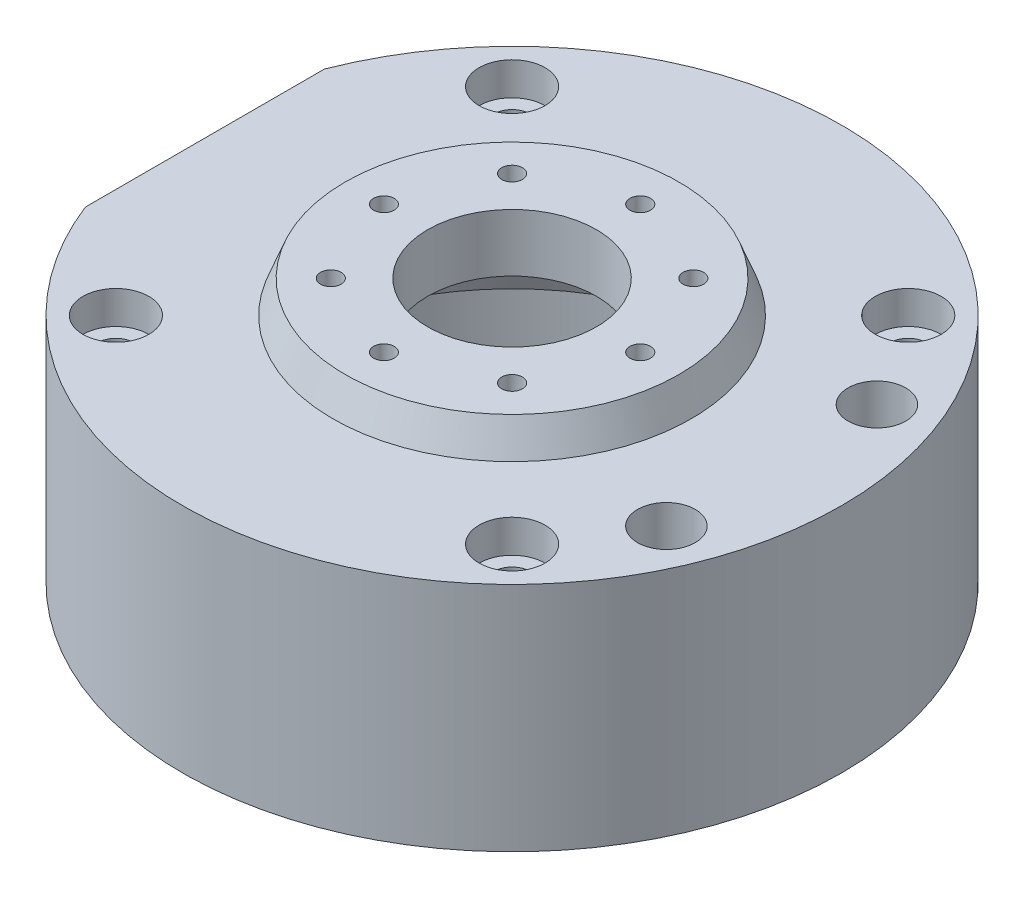
SolidWorks part; units mm, degrees
ref_plane "Front Plane" through (0, 0, 0) normal (0, 0, 1) x (1, 0, 0)
ref_plane "Top Plane" through (0, 0, 0) normal (0, 1, 0) x (1, 0, 0)
ref_plane "Right Plane" through (0, 0, 0) normal (1, 0, 0) x (0, 0, -1)
sketch "Sketch1" plane through (0, 0, 0) normal (0, 0, 1) x (1, 0, 0)
  line L0 (0, 10.5736) -> (0, -6.4838) construction
  line L1 (10.235, 32) -> (10.235, 25)
  line L2 (10.235, 25) -> (25, 25)
  line L3 (25, 25) -> (29.55, 10)
  line L4 (29.55, 10) -> (29.55, 0)
  line L5 (29.55, 0) -> (40, 0)
  line L6 (40, 0) -> (40, 28.1)
  line L7 (40, 28.1) -> (21.75, 28.1)
  line L8 (21.75, 28.1) -> (20.25, 32)
  line L9 (20.25, 32) -> (10.235, 32)
  dimension "D1" = 80
  dimension "D2" = 59.1
  dimension "D3" = 10
  dimension "D4" = 50
  dimension "D5" = 25
  dimension "D6" = 28.1
  dimension "D7" = 32
  dimension "D8" = 20.47
  dimension "D9" = 40.5
  dimension "D10" = 43.5
revolve "Revolve1" add sketch "Sketch1" angle 360 about L0
sketch "Sketch2" plane through (0, 28.1, 0) normal (0, 1, 0) x (1, 0, 0)
  line L1 (24.0416, -24.0416) -> (-24.0416, -24.0416) construction
  line L2 (24.0416, -24.0416) -> (24.0416, 24.0416) construction
  line L3 (24.0416, 24.0416) -> (-24.0416, 24.0416) construction
  line L4 (-24.0416, -24.0416) -> (-24.0416, 24.0416) construction
  line L5 (24.0416, -24.0416) -> (-24.0416, 24.0416) construction
  line L6 (24.0416, 24.0416) -> (-24.0416, -24.0416) construction
  point P0 (0, 0)
  dimension "D1" = 68
hole_wizard "CBORE for M4 SHCS1" positions "Sketch3" profile "Sketch4" counterbore size "M4" standard "ANSI Metric" end condition through all
sketch "Sketch3" plane through (0, 28.1, 0) normal (0, 1, 0) x (1, 0, 0)
  point P0 (-24.0416, 24.0416)
  point P3 (24.0416, 24.0416)
  point P6 (24.0416, -24.0416)
  point P9 (-24.0416, -24.0416)
sketch "Sketch4" plane through (-24.0416, 28.1, -24.0416) normal (1, 0, 0) x (0, 0, 1)
  line L0 (0, 0) -> (0, 28.1)
  line L1 (0, 28.1) -> (2.25, 28.1)
  line L3 (2.25, 28.1) -> (2.25, 4)
  line L4 (2.25, 4) -> (4, 4)
  line L5 (4, 4) -> (4, 0)
  line L7 (4, 0) -> (0, 0)
  line L11 (0, -6.35) -> (0, 107.95) construction
  dimension "Thru Hole Dia." = 4.5
  dimension "Thru Hole Depth" = 28.1
  dimension "C'Bore Dia." = 8
  dimension "C'Bore Depth" = 4
sketch "Sketch5" plane through (0, 32, 0) normal (0, 1, 0) x (1, 0, 0)
  line L0 (0, -15.5563) -> (15.5563, 0) construction
  line L1 (11, -11) -> (-11, -11) construction
  line L2 (11, -11) -> (11, 11) construction
  line L3 (11, 11) -> (-11, 11) construction
  line L4 (-11, -11) -> (-11, 11) construction
  line L5 (11, -11) -> (-11, 11) construction
  line L6 (11, 11) -> (-11, -11) construction
  line L7 (0, -15.5563) -> (-15.5563, 0) construction
  line L8 (15.5563, 0) -> (0, 15.5563) construction
  line L9 (-15.5563, 0) -> (0, 15.5563) construction
  line L10 (0, -15.5563) -> (0, 15.5563) construction
  line L11 (15.5563, 0) -> (-15.5563, 0) construction
  point P0 (0, 0)
  point P6 (0.9944, 16.7647)
  point P7 (0, 0)
  dimension "D1" = 22
hole_wizard "M3x0.5 Tapped Hole1" positions "Sketch6" profile "Sketch7" tap size "M3x0.5" standard "ANSI Metric" end condition through all
sketch "Sketch6" plane through (0, 32, 0) normal (0, 1, 0) x (1, 0, 0)
  point P0 (-11, 11)
  point P3 (11, 11)
  point P6 (11, -11)
  point P9 (-11, -11)
  point P12 (0, 15.5563)
  point P15 (15.5563, 0)
  point P18 (0, -15.5563)
  point P21 (-15.5563, 0)
sketch "Sketch7" plane through (-11, 32, -11) normal (1, 0, 0) x (0, 0, 1)
  line L0 (0, 0) -> (0, 32)
  line L1 (0, 32) -> (1.25, 32)
  line L2 (1.25, 32) -> (1.25, 0)
  line L5 (1.25, 0) -> (0, 0)
  line L11 (0, -6.35) -> (0, 107.95) construction
  dimension "Thru Tap Drill Dia." = 2.5
  dimension "Thru Tap Drill Depth" = 32
cosmetic thread "Hole Thread1" parameters "D2"=3
cosmetic thread "Hole Thread2" parameters "D2"=3
cosmetic thread "Hole Thread3" parameters "D2"=3
cosmetic thread "Hole Thread4" parameters "D2"=3
cosmetic thread "Hole Thread11" parameters "D2"=3
cosmetic thread "Hole Thread12" parameters "D2"=3
cosmetic thread "Hole Thread13" parameters "D2"=3
cosmetic thread "Hole Thread14" parameters "D2"=3
sketch "Sketch8" plane through (0, 28.1, 0) normal (0, 1, 0) x (1, 0, 0)
  line L0 (0, 0) -> (31.5087, 12.775)
  line L1 (31.5087, 12.775) -> (31.5087, -12.775)
  line L2 (31.5087, -12.775) -> (0, 0)
  line L3 (31.5087, -12.775) -> (37.0691, -15.0294)
  circle A0 centre (0, 0) radius 40 construction
  dimension "D1" = 25.55
  dimension "D2" = 6
hole_wizard "M8x1.0 Tapped Hole1" positions "Sketch9" profile "Sketch10" tap size "M8x1.0" standard "ANSI Metric"
sketch "Sketch9" plane through (0, 28.1, 0) normal (0, 1, 0) x (1, 0, 0)
  point P0 (31.5087, 12.775)
  point P3 (31.5087, -12.775)
cosmetic thread "Hole Thread5" parameters "D1"=16, "D2"=8
cosmetic thread "Hole Thread6" parameters "D1"=16, "D2"=8
sketch "Sketch10" plane through (31.5087, 28.1, -12.775) normal (1, 0, 0) x (0, 0, 1)
  line L0 (0, 0) -> (0, 23.103)
  line L1 (0, 23.103) -> (3.5, 21)
  line L2 (3.5, 21) -> (3.5, 0)
  line L5 (3.5, 0) -> (0, 0)
  line L10 (0, 23.103) -> (-3.5, 21) construction
  line L11 (0, -6.35) -> (0, 107.95) construction
  dimension "Tap Drill Dia." = 7
  dimension "Tap Drill Depth" = 21
  dimension "Drill Angle" = 118
hole_wizard "Hole1" positions "Sketch11" profile "Sketch12" legacy end condition through all
sketch "Sketch11" plane through (0, 0, 0) normal (0, -1, 0) x (-1, 0, 0)
  point P0 (-31.5087, -12.775)
  point P3 (-31.5087, 12.775)
sketch "Sketch12" plane through (31.5087, 0, 12.775) normal (1, 0, 0) x (0, 0, -1)
  line L0 (0, 0) -> (0, 32)
  line L1 (0, 32) -> (2.2, 32)
  line L2 (2.2, 32) -> (2.2, 1.27)
  line L3 (2.2, 1.27) -> (3.925, 1.27)
  line L4 (3.925, 1.27) -> (3.925, 0)
  line L5 (3.925, 0) -> (0, 0)
  line L6 (0, 110) -> (0, -10) construction
  dimension "Diameter" = 4.4
  dimension "Depth" = 32
  dimension "C-Bore Diameter" = 7.85
  dimension "C-Bore Depth" = 1.27
sketch "Sketch13" plane through (0, 0, 0) normal (0, -1, 0) x (1, 0, 0)
  line L0 (-37.2794, 14.5) -> (-37.2794, -14.5)
  circle A0 centre (0, 0) radius 40 construction
  arc A1 (-37.2794, 14.5) -> (-37.2794, -14.5) centre (0, 0) ccw
  dimension "D1" = 29
extrude "Cut-Extrude1" cut sketch "Sketch13" against normal through all and the other way through all
sketch "Sketch14" plane through (-37.2794, 0, 0) normal (-1, 0, 0) x (0, 0, 1)
  line L0 (0, 0) -> (14.5, 0) construction
  line L1 (-14.5, 0) -> (14.5, 0) construction
  line L2 (0, 0) -> (0, 14.5) construction
  line L3 (-7, 7.3586) -> (-7, 0)
  line L4 (11, 3.5) -> (-11, 3.5) construction
  line L5 (11, 3.5) -> (11, 25.5) construction
  line L6 (11, 25.5) -> (-11, 25.5) construction
  line L7 (-11, 3.5) -> (-11, 25.5) construction
  line L8 (11, 3.5) -> (-11, 25.5) construction
  line L9 (11, 25.5) -> (-11, 3.5) construction
  line L10 (-7, 0) -> (7, 0)
  line L11 (7, 0) -> (7, 7.3586)
  arc A0 (7, 7.3586) -> (-7, 7.3586) centre (0, 14.5) ccw
  point P10 (-10, 14.5)
  point P14 (-10, 14.5)
  point P16 (-9.5664, 10.3351)
  point P17 (0, 0)
  point P18 (0, 0)
  point P19 (2.6855, 10.1632)
  point P20 (-2.5415, 10.3402)
  dimension "D3" = 10
  dimension "D1" = 22
  dimension "D2" = 14
extrude "Cut-Extrude2" cut sketch "Sketch14" against normal up to next
hole_wizard "M3x0.5 Tapped Hole2" positions "Sketch15" profile "Sketch16" tap size "M3x0.5" standard "ANSI Metric"
sketch "Sketch15" plane through (-37.2794, 0, 0) normal (-1, 0, 0) x (0, 0, 1)
  point P0 (-11, 25.5)
  point P3 (-11, 3.5)
  point P6 (11, 3.5)
  point P9 (11, 25.5)
sketch "Sketch16" plane through (-37.2794, 25.5, -11) normal (0, 1, 0) x (0, 0, 1)
  line L0 (0, 0) -> (0, 8.2511)
  line L1 (0, 8.2511) -> (1.25, 7.5)
  line L2 (1.25, 7.5) -> (1.25, 0)
  line L5 (1.25, 0) -> (0, 0)
  line L10 (0, 8.2511) -> (-1.25, 7.5) construction
  line L11 (0, -6.35) -> (0, 107.95) construction
  dimension "Tap Drill Dia." = 2.5
  dimension "Tap Drill Depth" = 7.5
  dimension "Drill Angle" = 118
cosmetic thread "Hole Thread7" parameters "D1"=6, "D2"=3
cosmetic thread "Hole Thread8" parameters "D1"=6, "D2"=3
cosmetic thread "Hole Thread9" parameters "D1"=6, "D2"=3
cosmetic thread "Hole Thread10" parameters "D1"=6, "D2"=3
